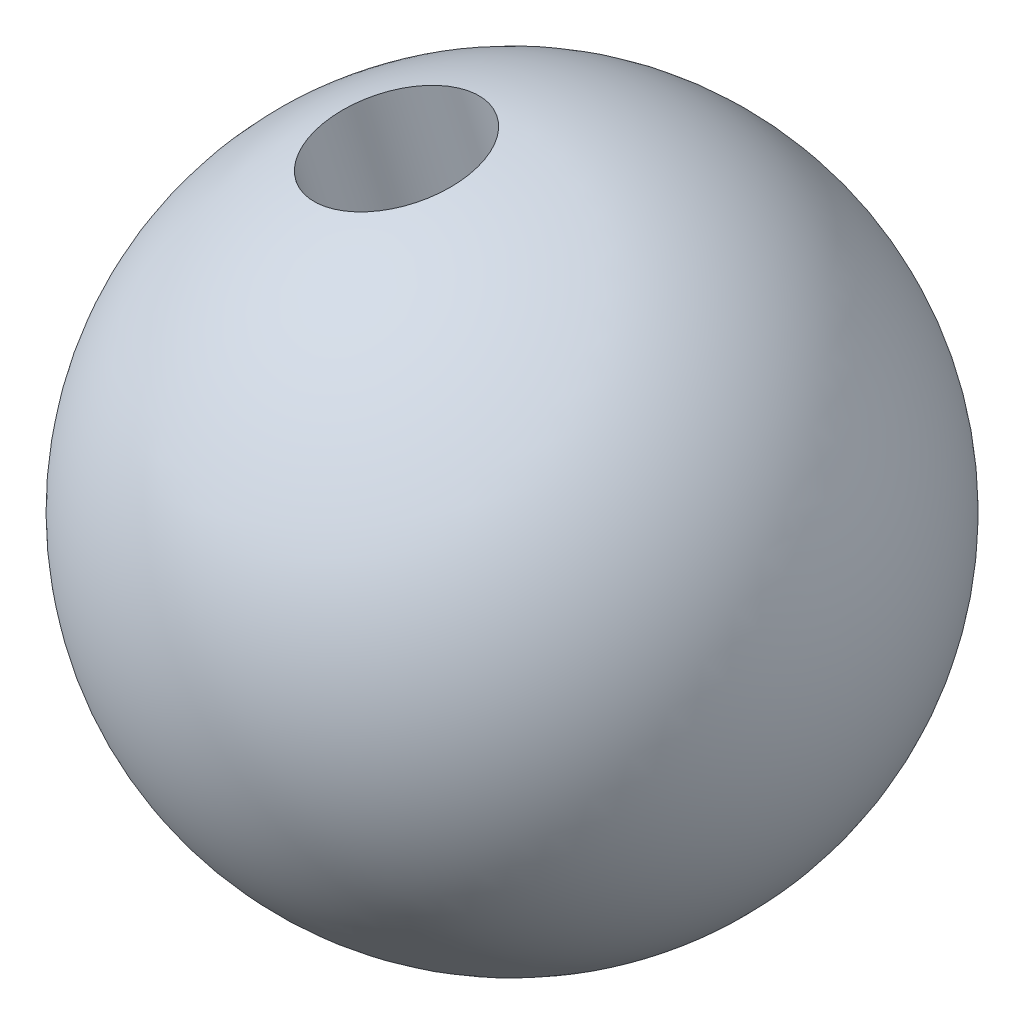
SolidWorks part; units mm, degrees
material "AISI 316L"
ref_plane "Piano frontale" through (0, 0, 0) normal (0, 0, 1) x (1, 0, 0)
ref_plane "Piano superiore" through (0, 0, 0) normal (0, 1, 0) x (1, 0, 0)
ref_plane "Piano destro" through (0, 0, 0) normal (1, 0, 0) x (0, 0, -1)
sketch "Schizzo1" plane through (0, 0, 0) normal (0, 0, 1) x (1, 0, 0)
  line L0 (0.6636, 14.9853) -> (-0.6636, -14.9853)
  arc A0 (0.6636, 14.9853) -> (-0.6636, -14.9853) centre (0, 0) ccw
  dimension "D1" = 30
revolve "Rivoluzione1" add sketch "Schizzo1" angle 360 about L0
hole_wizard "Preforo da maschiare M8x1.25-1" positions "Schizzo3D1" profile "Schizzo2" hole size "M8x1.25" standard "Ansi Metric"
sketch3d "Schizzo3D1"
  point P0 (0, 0, 0)
  point P3 (0, 0, 0)
  point P5 (-2.9015, 14.5029, 2.4995)
sketch "Schizzo2" plane through (-2.9015, 14.5029, 2.4995) normal (0.707, 0.0196, 0.707) x (-0.6803, -0.2546, 0.6873)
  line L0 (0, 0) -> (0, 15)
  line L1 (0, 15) -> (3.4, 12.9571)
  line L2 (3.4, 12.9571) -> (3.4, 0)
  line L5 (3.4, 0) -> (0, 0)
  line L10 (0, 15) -> (-3.4, 12.9571) construction
  line L11 (0, -6.35) -> (0, 107.95) construction
  dimension "Hole Dia." = 6.8
  dimension "Hole Depth" = 15
  dimension "Drill Angle" = 118
